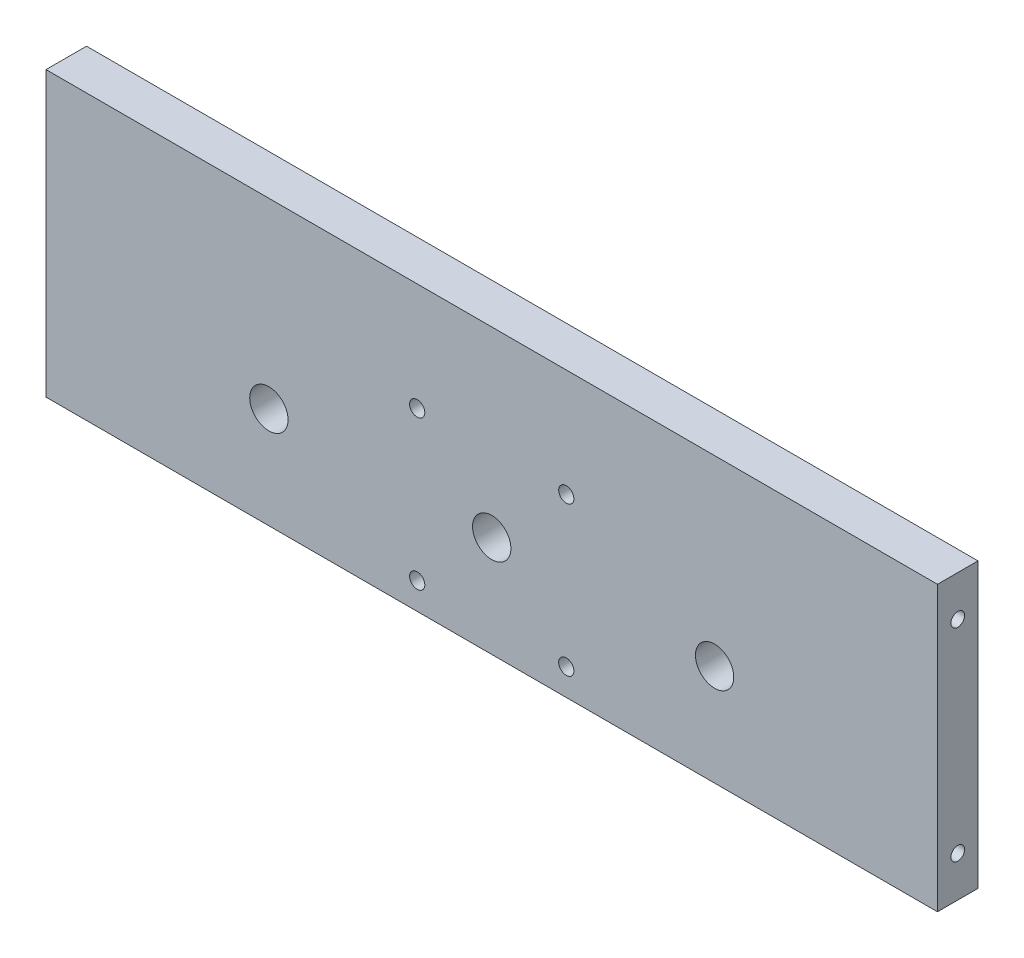
SolidWorks part; units mm, degrees
ref_plane "Front Plane" through (0, 0, 0) normal (0, 0, 1) x (1, 0, 0)
ref_plane "Top Plane" through (0, 0, 0) normal (0, 1, 0) x (1, 0, 0)
ref_plane "Right Plane" through (0, 0, 0) normal (1, 0, 0) x (0, 0, -1)
sketch "Sketch1" plane through (0, 0, 0) normal (0, 0, 1) x (1, 0, 0)
  line L1 (0, 0) -> (279.4, 0)
  line L2 (0, 0) -> (0, 88.9)
  line L3 (0, 88.9) -> (279.4, 88.9)
  line L4 (279.4, 0) -> (279.4, 88.9)
  dimension "D1" = 88.9
  dimension "D2" = 279.4
extrude "Boss-Extrude1" add sketch "Sketch1" along normal blind 12.7
sketch "Sketch2" plane through (279.4, 0, 0) normal (1, 0, 0) x (0, 0, -1)
  line L0 (-12.7, 0) -> (-12.7, 88.9) construction
  line L2 (-12.7, 0) -> (0, 0) construction
  line L3 (-12.7, 88.9) -> (0, 88.9) construction
  circle A0 centre (-6.35, 76.2) radius 2.1463
  circle A1 centre (-6.35, 12.7) radius 2.1463
  dimension "D5" = 4.2926
  dimension "D6" = 4.2926
  dimension "D1" = 6.35
  dimension "D2" = 6.35
  dimension "D3" = 12.7
  dimension "D4" = 12.7
extrude "Cut-Extrude1" cut sketch "Sketch2" against normal blind 38.1
sketch "Sketch3" plane through (0, 0, 0) normal (-1, 0, 0) x (0, 0, 1)
  line L0 (0, 88.9) -> (0, 0) construction
  line L1 (12.7, 88.9) -> (0, 88.9) construction
  line L2 (12.7, 0) -> (0, 0) construction
  circle A0 centre (6.35, 76.2) radius 2.1463
  circle A1 centre (6.35, 12.7) radius 2.1463
  dimension "D5" = 4.2926
  dimension "D6" = 4.2926
  dimension "D1" = 6.35
  dimension "D2" = 6.35
  dimension "D3" = 12.7
  dimension "D4" = 12.7
extrude "Cut-Extrude2" cut sketch "Sketch3" against normal blind 38.1
sketch "Sketch4" plane through (0, 0, 0) normal (0, 0, -1) x (-1, 0, 0)
  line L0 (0, 0) -> (-279.4, 0) construction
  line L1 (0, 88.9) -> (0, 0) construction
  line L2 (-279.4, 0) -> (-279.4, 88.9) construction
  circle A0 centre (-209.55, 31.75) radius 6.0071
  circle A1 centre (-139.7, 31.75) radius 6.0071
  circle A2 centre (-69.85, 31.75) radius 6.0071
  dimension "D7" = 12.0142
  dimension "D8" = 12.0142
  dimension "D9" = 12.0142
  dimension "D1" = 31.75
  dimension "D2" = 31.75
  dimension "D3" = 31.75
  dimension "D4" = 139.7
  dimension "D5" = 69.85
  dimension "D6" = 69.85
extrude "Cut-Extrude3" cut sketch "Sketch4" against normal through all
sketch "Sketch5" plane through (0, 0, 0) normal (0, 0, 1) x (1, 0, 0)
  line L0 (111.4171, 54.4767) -> (111.4171, 9.0233)
  line L1 (116.9733, 3.4671) -> (120.9165, 3.4671)
  line L2 (120.9165, 3.4671) -> (120.9165, 7.4358)
  line L3 (127.5205, 7.4358) -> (127.5205, 3.4671)
  line L4 (127.5205, 3.4671) -> (151.8795, 3.4671)
  line L5 (151.8795, 3.4671) -> (151.8795, 7.4358)
  line L6 (158.4835, 7.4358) -> (158.4835, 3.4671)
  line L7 (158.4835, 3.4671) -> (162.4266, 3.4671)
  line L8 (167.9829, 9.0233) -> (167.9829, 54.4766)
  line L9 (162.4266, 60.0329) -> (158.4835, 60.0329)
  line L10 (158.4835, 60.0329) -> (158.4835, 56.0642)
  line L11 (151.8795, 56.0641) -> (151.8795, 60.0329)
  line L12 (151.8795, 60.0329) -> (127.5205, 60.0329)
  line L13 (127.5205, 60.0329) -> (127.5205, 56.0641)
  line L14 (120.9165, 56.0642) -> (120.9165, 60.0329)
  line L15 (120.9165, 60.0329) -> (116.9733, 60.0329)
  circle A0 centre (163.0617, 55.1116) radius 2.3813
  circle A1 centre (116.3383, 55.1116) radius 2.3812
  circle A2 centre (116.3383, 8.3883) radius 2.3812
  circle A3 centre (163.0617, 8.3883) radius 2.3813
  arc A4 (111.4171, 9.0233) -> (116.9733, 3.4671) centre (116.9733, 9.0233) ccw
  arc A5 (127.5205, 7.4358) -> (120.9165, 7.4358) centre (124.2185, 7.4358) ccw
  arc A6 (158.4835, 7.4358) -> (151.8795, 7.4358) centre (155.1815, 7.4358) ccw
  arc A7 (162.4266, 3.4671) -> (167.9829, 9.0233) centre (162.4266, 9.0233) ccw
  arc A8 (167.9829, 54.4766) -> (162.4266, 60.0329) centre (162.4266, 54.4766) ccw
  arc A9 (151.8795, 56.0641) -> (158.4835, 56.0642) centre (155.1815, 56.0642) ccw
  arc A10 (120.9165, 56.0642) -> (127.5205, 56.0641) centre (124.2185, 56.0641) ccw
  arc A11 (116.9733, 60.0329) -> (111.4171, 54.4767) centre (116.9733, 54.4767) ccw
extrude "Cut-Extrude4" cut sketch "Sketch5" along normal through all contours A2 | A3 | A1 | A0
